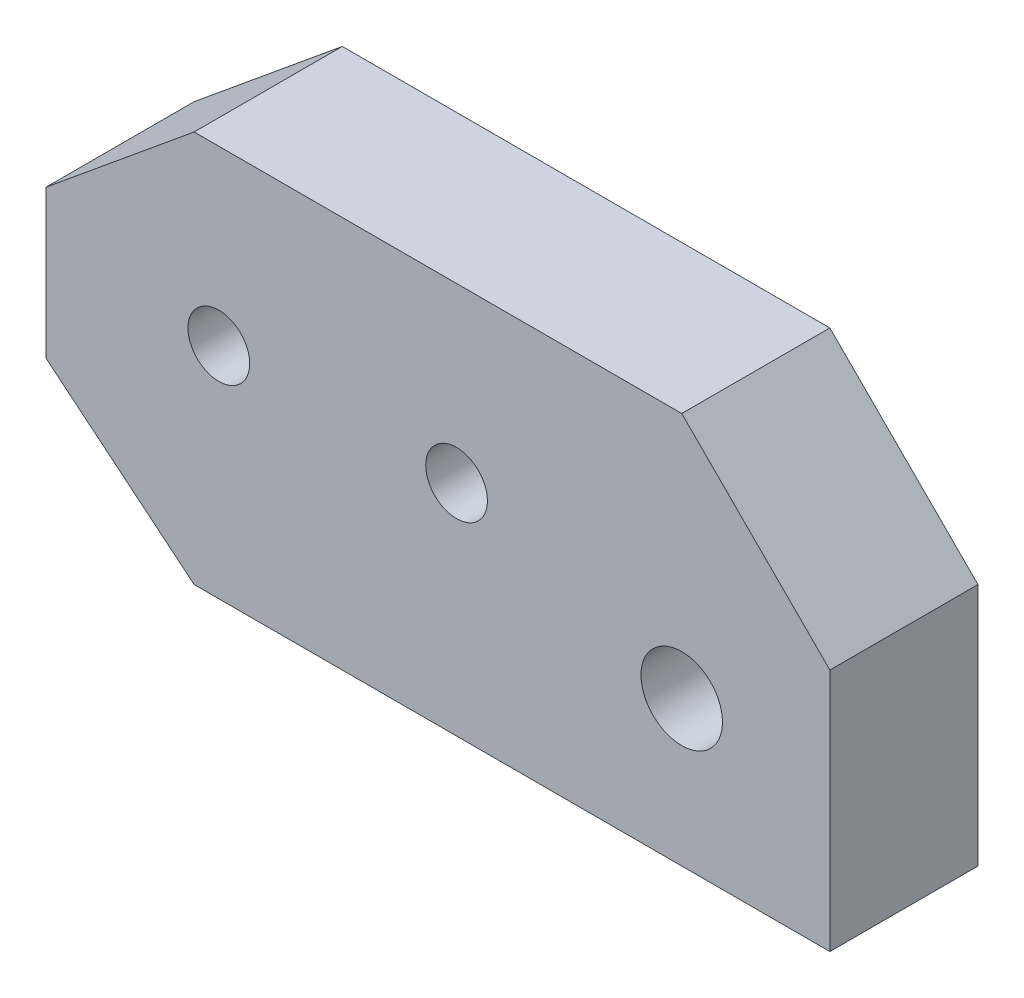
SolidWorks part; units mm, degrees
ref_plane "Front Plane" through (0, 0, 0) normal (0, 0, 1) x (1, 0, 0)
ref_plane "Top Plane" through (0, 0, 0) normal (0, 1, 0) x (1, 0, 0)
ref_plane "Right Plane" through (0, 0, 0) normal (1, 0, 0) x (0, 0, -1)
sketch "Sketch2" plane through (0, 0, 0) normal (0, 0, 1) x (1, 0, 0)
  line L0 (-19.75, 15.875) -> (-31.75, 15.875) construction
  line L1 (31.75, -15.875) -> (-19.75, -15.875)
  line L2 (31.75, -15.875) -> (31.75, 3.875)
  line L3 (19.75, 15.875) -> (-19.75, 15.875)
  line L5 (31.75, -15.875) -> (-31.75, 15.875) construction
  line L6 (31.75, 15.875) -> (-31.75, -15.875) construction
  line L7 (-31.75, 6) -> (-19.75, 15.875)
  line L8 (-31.75, -6) -> (-19.75, -15.875)
  line L9 (-31.75, 0) -> (0, 0) construction
  line L10 (-19.75, -15.875) -> (-31.75, -15.875) construction
  line L12 (-31.75, 15.875) -> (-31.75, 6) construction
  line L13 (-31.75, 6) -> (-31.75, -6)
  line L14 (-31.75, -6) -> (-31.75, -15.875) construction
  line L15 (19.75, 15.875) -> (31.75, 3.875)
  line L16 (31.75, 15.875) -> (19.75, 15.875) construction
  line L17 (31.75, 3.875) -> (31.75, 15.875) construction
  point P0 (0, 0)
  dimension "D1" = 63.5
  dimension "D2" = 31.75
  dimension "D3" = 12
  dimension "D4" = 12
  dimension "D5" = 12
  dimension "D6" = 12
extrude "Boss-Extrude1" add sketch "Sketch2" along normal mid plane 12
hole_wizard "M6x1.0 Tapped Hole1" positions "Sketch5" profile "Sketch4" tap size "M6x1.0" standard "ANSI Metric" end condition through all
sketch "Sketch5" plane through (0, 0, -6) normal (0, 0, -1) x (-1, 0, 0)
  line L1 (31.75, 6) -> (31.75, -6) construction
  line L2 (-19.75, 15.875) -> (19.75, 15.875) construction
  line L3 (19.75, 15.875) -> (31.75, 6) construction
  point P0 (17.75, 1.875)
  point P2 (-1.51, 1.875)
  point P5 (20.1451, -0.9796)
  point P6 (0, 0)
  point P7 (0, 0)
  point P13 (0, 0)
  point P14 (20, 3.3808)
  dimension "D1" = 19.26
  dimension "D2" = 14
  dimension "D3" = 14
  dimension "D4" = 12.0811
sketch "Sketch4" plane through (-17.75, 1.875, -6) normal (1, 0, 0) x (0, 1, 0)
  line L0 (0, 0) -> (0, 12)
  line L1 (0, 12) -> (2.5, 12)
  line L2 (2.5, 12) -> (2.5, 0)
  line L5 (2.5, 0) -> (0, 0)
  line L11 (0, -6.35) -> (0, 107.95) construction
  dimension "Thru Tap Drill Dia." = 5
  dimension "Thru Tap Drill Depth" = 12
cosmetic thread "Hole Thread1"
cosmetic thread "Hole Thread2"
hole_wizard "M6 Clearance Hole1" positions "Sketch8" profile "Sketch7" hole size "M6" standard "ANSI Metric" end condition through all
sketch "Sketch8" plane through (0, 0, -6) normal (0, 0, -1) x (-1, 0, 0)
  line L1 (19.75, -15.875) -> (-31.75, -15.875) construction
  line L2 (-31.75, -15.875) -> (-31.75, 3.875) construction
  point P0 (-19.7484, -4.125)
  dimension "D1" = 11.75
  dimension "D2" = 12.0016
sketch "Sketch7" plane through (19.7484, -4.125, -6) normal (1, 0, 0) x (0, 1, 0)
  line L0 (0, 0) -> (0, 12)
  line L1 (0, 12) -> (3.3, 12)
  line L2 (3.3, 12) -> (3.3, 0)
  line L5 (3.3, 0) -> (0, 0)
  line L11 (0, -6.35) -> (0, 107.95) construction
  dimension "Thru Hole Dia." = 6.6
  dimension "Thru Hole Depth" = 12
